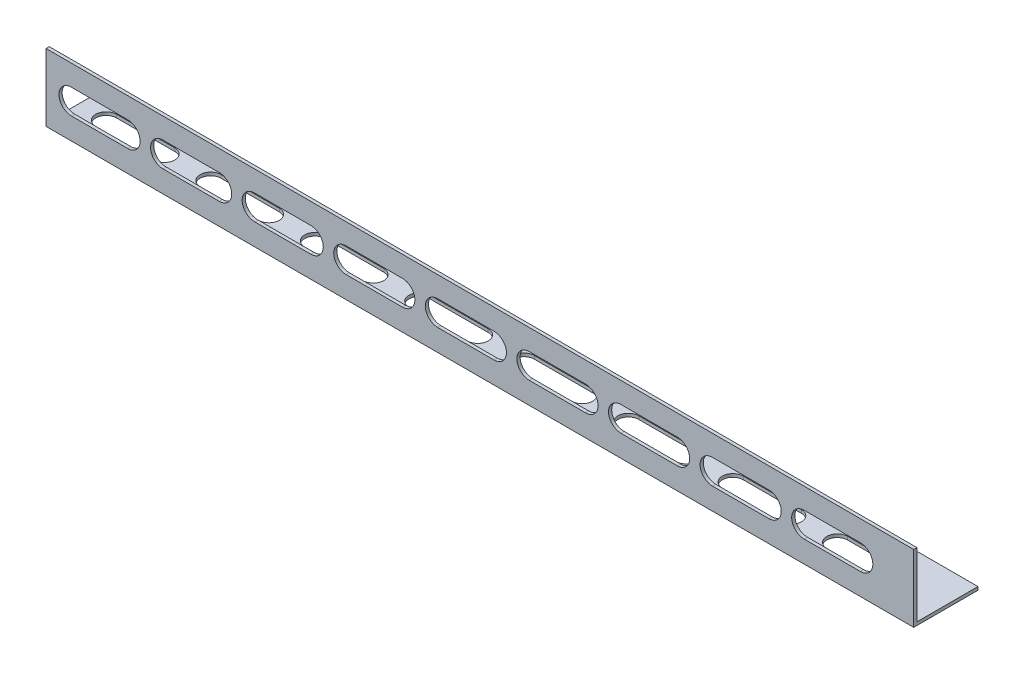
SolidWorks part; units mm, degrees
ref_plane "Front Plane" through (0, 0, 0) normal (0, 0, 1) x (1, 0, 0)
ref_plane "Top Plane" through (0, 0, 0) normal (0, 1, 0) x (1, 0, 0)
ref_plane "Right Plane" through (0, 0, 0) normal (1, 0, 0) x (0, 0, -1)
sketch "Sketch1" plane through (0, 0, 0) normal (0, 1, 0) x (1, 0, 0)
  line L1 (-75, 20) -> (75, 20)
  line L2 (-75, 20) -> (-75, -20)
  line L3 (-75, -20) -> (75, -20)
  line L4 (75, 20) -> (75, -20)
  line L5 (-75, 20) -> (75, -20) construction
  line L6 (-75, -20) -> (75, 20) construction
  point P0 (0, 0)
  dimension "D1" = 150
  dimension "D2" = 40
extrude "Boss-Extrude1" add sketch "Sketch1" along normal blind 2
sketch "Sketch2" plane through (0, 2, 0) normal (0, 1, 0) x (1, 0, 0)
  line L0 (75, -20) -> (75, 20) construction
  line L1 (-75, -20) -> (75, -20)
  line L2 (-75, -20) -> (-75, -18)
  line L3 (-75, -18) -> (75, -18)
  line L4 (75, -20) -> (75, -18)
  dimension "D1" = 2
extrude "Boss-Extrude2" add sketch "Sketch2" along normal blind 40
sketch "Sketch5" plane through (75, 0, 0) normal (1, 0, 0) x (0, 0, -1)
  line L12 (-20, 0) -> (20, 0)
  line L13 (20, 0) -> (20, 2)
  line L14 (20, 2) -> (-18, 2)
  line L15 (-18, 2) -> (-18, 42)
  line L16 (-18, 42) -> (-20, 42)
  line L17 (-20, 42) -> (-20, 0)
  line L18 (-20, 0) -> (20, 0)
  line L19 (20, 0) -> (20, 2)
  line L20 (20, 2) -> (-18, 2)
  line L21 (-18, 2) -> (-18, 42)
  line L22 (-18, 42) -> (-20, 42)
  line L23 (-20, 42) -> (-20, 0)
  dimension "D1" = 0
extrude "Boss-Extrude3" add sketch "Sketch5" along normal blind 390
sketch "Sketch6" plane through (0, 0, 0) normal (0, -1, 0) x (1, 0, 0)
  line L0 (7.4206, 6.4938) -> (43.6971, 6.4938)
  line L1 (-57.5794, 6.4938) -> (-21.3029, 6.4938)
  line L3 (-57.5794, -6.4938) -> (-21.3029, -6.4938)
  line L5 (-57.5794, 6.4938) -> (-21.3029, -6.4938) construction
  line L6 (-57.5794, -6.4938) -> (-21.3029, 6.4938) construction
  line L7 (7.4206, -6.4938) -> (43.6971, -6.4938)
  line L8 (72.4206, 6.4938) -> (108.6971, 6.4938)
  line L9 (72.4206, -6.4938) -> (108.6971, -6.4938)
  line L10 (137.4206, 6.4938) -> (173.6971, 6.4938)
  line L11 (137.4206, -6.4938) -> (173.6971, -6.4938)
  line L12 (202.4206, 6.4938) -> (238.6971, 6.4938)
  line L13 (202.4206, -6.4938) -> (238.6971, -6.4938)
  line L14 (267.4206, 6.4938) -> (303.6971, 6.4938)
  line L15 (267.4206, -6.4938) -> (303.6971, -6.4938)
  line L16 (332.4206, 6.4938) -> (368.6971, 6.4938)
  line L17 (332.4206, -6.4938) -> (368.6971, -6.4938)
  line L18 (397.4206, 6.4938) -> (433.6971, 6.4938)
  line L19 (397.4206, -6.4938) -> (433.6971, -6.4938)
  arc A0 (-21.3029, 6.4938) -> (-21.3029, -6.4938) centre (-21.3029, 0) cw
  arc A1 (-57.5794, 6.4938) -> (-57.5794, -6.4938) centre (-57.5794, 0) ccw
  arc A2 (43.6971, 6.4938) -> (43.6971, -6.4938) centre (43.6971, 0) cw
  arc A3 (7.4206, 6.4938) -> (7.4206, -6.4938) centre (7.4206, 0) ccw
  arc A4 (108.6971, 6.4938) -> (108.6971, -6.4938) centre (108.6971, 0) cw
  arc A5 (72.4206, 6.4938) -> (72.4206, -6.4938) centre (72.4206, 0) ccw
  arc A6 (173.6971, 6.4938) -> (173.6971, -6.4938) centre (173.6971, 0) cw
  arc A7 (137.4206, 6.4938) -> (137.4206, -6.4938) centre (137.4206, 0) ccw
  arc A8 (238.6971, 6.4938) -> (238.6971, -6.4938) centre (238.6971, 0) cw
  arc A9 (202.4206, 6.4938) -> (202.4206, -6.4938) centre (202.4206, 0) ccw
  arc A10 (303.6971, 6.4938) -> (303.6971, -6.4938) centre (303.6971, 0) cw
  arc A11 (267.4206, 6.4938) -> (267.4206, -6.4938) centre (267.4206, 0) ccw
  arc A12 (368.6971, 6.4938) -> (368.6971, -6.4938) centre (368.6971, 0) cw
  arc A13 (332.4206, 6.4938) -> (332.4206, -6.4938) centre (332.4206, 0) ccw
  arc A14 (433.6971, 6.4938) -> (433.6971, -6.4938) centre (433.6971, 0) cw
  arc A15 (397.4206, 6.4938) -> (397.4206, -6.4938) centre (397.4206, 0) ccw
  point P0 (-39.4411, 0)
  dimension "D1" = 8
extrude "Cut-Extrude1" cut sketch "Sketch6" against normal blind 10
sketch "Sketch7" plane through (0, 0, 20) normal (0, 0, 1) x (1, 0, 0)
  line L0 (-2.2014, 29.0226) -> (32.7986, 29.0226)
  line L1 (-59.2014, 29.0226) -> (-24.2014, 29.0226)
  line L3 (-59.2014, 13.5225) -> (-24.2014, 13.5225)
  line L5 (-59.2014, 29.0226) -> (-24.2014, 13.5225) construction
  line L6 (-59.2014, 13.5225) -> (-24.2014, 29.0226) construction
  line L7 (-2.2014, 13.5225) -> (32.7986, 13.5225)
  line L8 (54.7986, 29.0226) -> (89.7986, 29.0226)
  line L9 (54.7986, 13.5225) -> (89.7986, 13.5225)
  line L10 (111.7986, 29.0226) -> (146.7986, 29.0226)
  line L11 (111.7986, 13.5225) -> (146.7986, 13.5225)
  line L12 (168.7986, 29.0226) -> (203.7986, 29.0226)
  line L13 (168.7986, 13.5225) -> (203.7986, 13.5225)
  line L14 (225.7986, 29.0226) -> (260.7986, 29.0226)
  line L15 (225.7986, 13.5225) -> (260.7986, 13.5225)
  line L16 (282.7986, 29.0226) -> (317.7986, 29.0226)
  line L17 (282.7986, 13.5225) -> (317.7986, 13.5225)
  line L18 (339.7986, 29.0226) -> (374.7986, 29.0226)
  line L19 (339.7986, 13.5225) -> (374.7986, 13.5225)
  line L20 (396.7986, 29.0226) -> (431.7986, 29.0226)
  line L21 (396.7986, 13.5225) -> (431.7986, 13.5225)
  arc A0 (-24.2014, 29.0226) -> (-24.2014, 13.5225) centre (-24.2014, 21.2726) cw
  arc A1 (-59.2014, 29.0226) -> (-59.2014, 13.5225) centre (-59.2014, 21.2726) ccw
  arc A2 (32.7986, 29.0226) -> (32.7986, 13.5225) centre (32.7986, 21.2726) cw
  arc A3 (-2.2014, 29.0226) -> (-2.2014, 13.5225) centre (-2.2014, 21.2726) ccw
  arc A4 (89.7986, 29.0226) -> (89.7986, 13.5225) centre (89.7986, 21.2726) cw
  arc A5 (54.7986, 29.0226) -> (54.7986, 13.5225) centre (54.7986, 21.2726) ccw
  arc A6 (146.7986, 29.0226) -> (146.7986, 13.5225) centre (146.7986, 21.2726) cw
  arc A7 (111.7986, 29.0226) -> (111.7986, 13.5225) centre (111.7986, 21.2726) ccw
  arc A8 (203.7986, 29.0226) -> (203.7986, 13.5225) centre (203.7986, 21.2726) cw
  arc A9 (168.7986, 29.0226) -> (168.7986, 13.5225) centre (168.7986, 21.2726) ccw
  arc A10 (260.7986, 29.0226) -> (260.7986, 13.5225) centre (260.7986, 21.2726) cw
  arc A11 (225.7986, 29.0226) -> (225.7986, 13.5225) centre (225.7986, 21.2726) ccw
  arc A12 (317.7986, 29.0226) -> (317.7986, 13.5225) centre (317.7986, 21.2726) cw
  arc A13 (282.7986, 29.0226) -> (282.7986, 13.5225) centre (282.7986, 21.2726) ccw
  arc A14 (374.7986, 29.0226) -> (374.7986, 13.5225) centre (374.7986, 21.2726) cw
  arc A15 (339.7986, 29.0226) -> (339.7986, 13.5225) centre (339.7986, 21.2726) ccw
  arc A16 (431.7986, 29.0226) -> (431.7986, 13.5225) centre (431.7986, 21.2726) cw
  arc A17 (396.7986, 29.0226) -> (396.7986, 13.5225) centre (396.7986, 21.2726) ccw
  point P0 (-41.7014, 21.2726)
  dimension "D1" = 35
  dimension "D2" = 9
extrude "Cut-Extrude2" cut sketch "Sketch7" against normal blind 10
